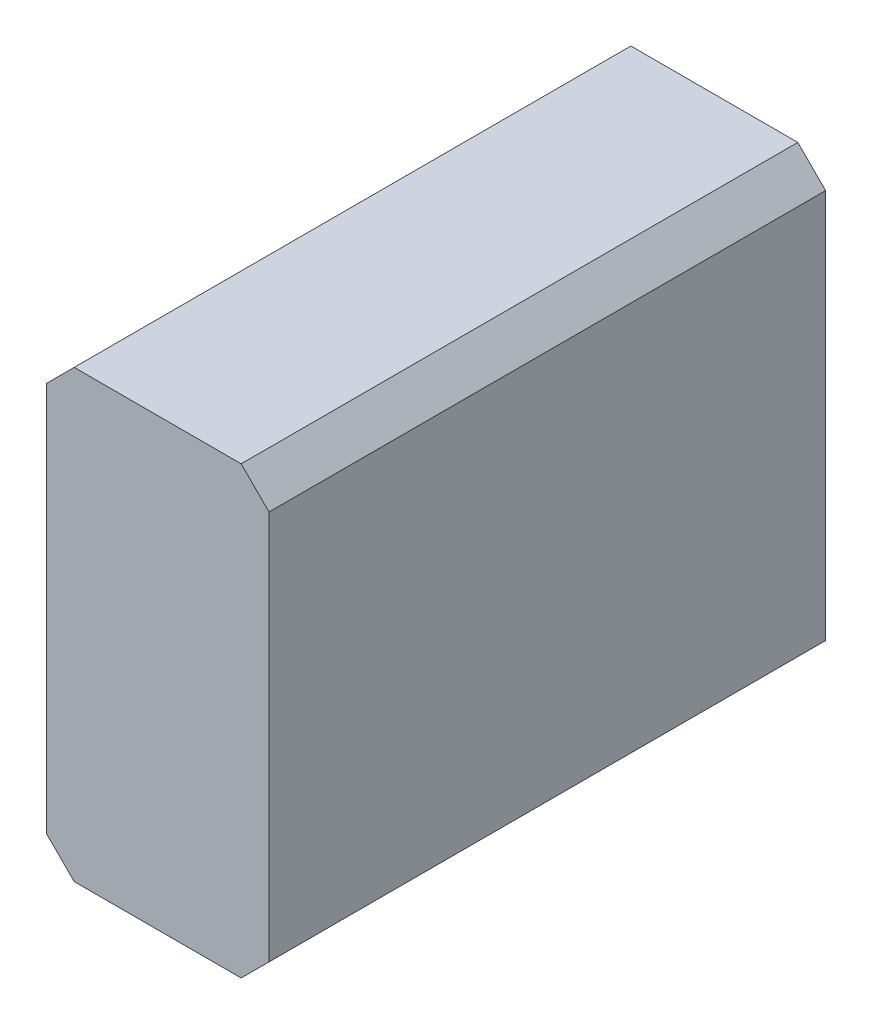
SolidWorks part; units mm, degrees
ref_plane "Front Plane" through (0, 0, 0) normal (0, 0, 1) x (1, 0, 0)
ref_plane "Top Plane" through (0, 0, 0) normal (0, 1, 0) x (1, 0, 0)
ref_plane "Right Plane" through (0, 0, 0) normal (1, 0, 0) x (0, 0, -1)
sketch "Sketch1" plane through (0, 0, 0) normal (0, 0, 1) x (1, 0, 0)
  line L0 (0, 4) -> (0, -4) construction
  line L1 (-2, 4) -> (2, 4)
  line L2 (-2, 4) -> (-2, -4)
  line L3 (-2, -4) -> (2, -4)
  line L4 (2, 4) -> (2, -4)
  line L5 (-2, 0) -> (2, 0) construction
  dimension "D1" = 4
  dimension "D2" = 8
extrude "Boss-Extrude1" add sketch "Sketch1" along normal blind 10
chamfer "Chamfer1" distance 0.5 angle 45 4 edges at (-2, -4, 5) (2, -4, 5) (2, 4, 5) (-2, 4, 5)
